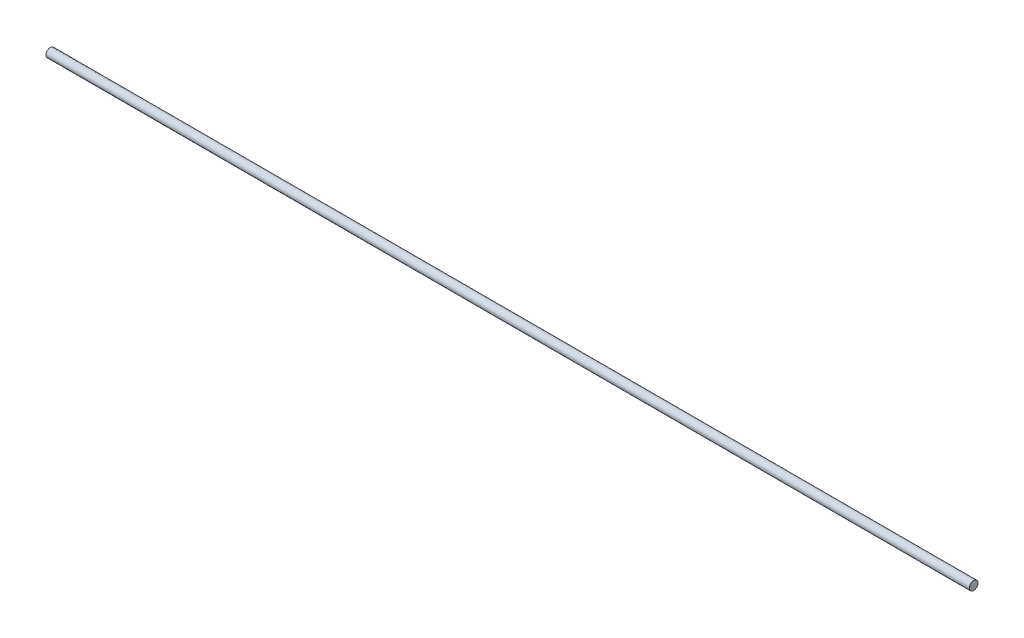
SolidWorks part; units mm, degrees
ref_plane "Front Plane" through (0, 0, 0) normal (0, 0, 1) x (1, 0, 0)
ref_plane "Top Plane" through (0, 0, 0) normal (0, 1, 0) x (1, 0, 0)
ref_plane "Right Plane" through (0, 0, 0) normal (1, 0, 0) x (0, 0, -1)
sketch "Sketch2" plane through (0, 0, 0) normal (1, 0, 0) x (0, 0, -1)
  circle A0 centre (0, 0) radius 6.35
  point P3 (0, 0)
  dimension "D1" = 12.7
extrude "Boss-Extrude1" add sketch "Sketch2" along normal blind 1346.454
equation "\"Load\"= 300"
equation "\"Diameter\"= .5"
equation "\"E\" = 9 * ( 10 ^ 6 )"
equation "\"Deflection\"= .009"
equation "\"Area\"= ( \"Diameter\" ^ 2 ) * ( pi / 4 )"
equation "\"Length\"= ( \"Deflection\" * \"Area\" * \"E\" ) / ( \"Load\" )"
